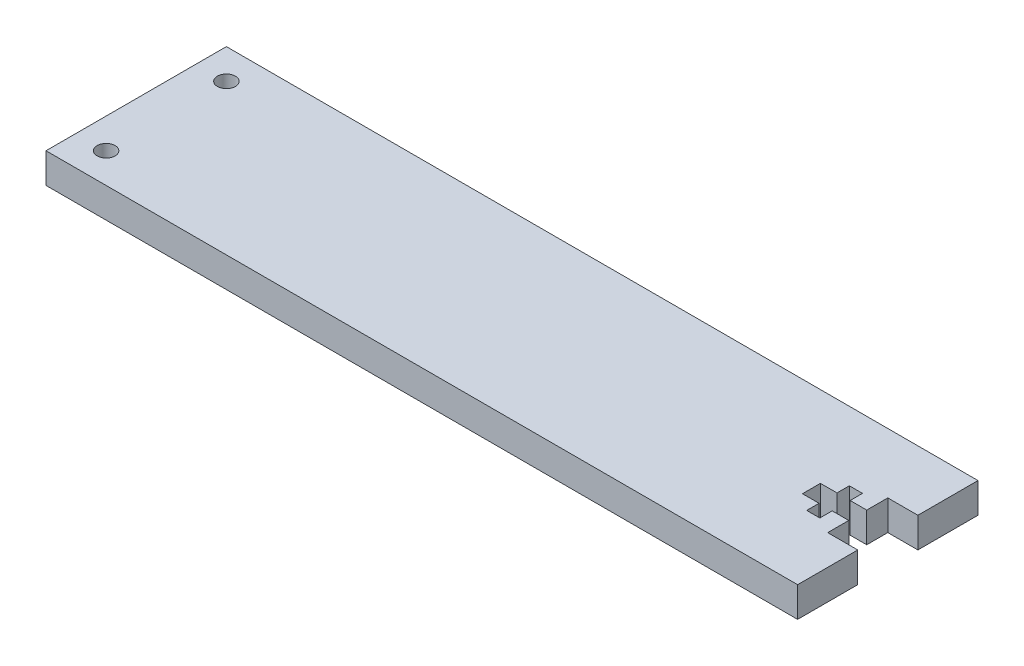
SolidWorks part; units mm, degrees
material "Beech"
ref_plane "Front Plane" through (0, 0, 0) normal (0, 0, 1) x (1, 0, 0)
ref_plane "Top Plane" through (0, 0, 0) normal (0, 1, 0) x (1, 0, 0)
ref_plane "Right Plane" through (0, 0, 0) normal (1, 0, 0) x (0, 0, -1)
sketch "Sketch1" plane through (0, 0, 0) normal (0, 1, 0) x (1, 0, 0)
  line L1 (-79.375, -19.05) -> (79.375, -19.05)
  line L2 (-79.375, -19.05) -> (-79.375, 19.05)
  line L3 (-79.375, 19.05) -> (79.375, 19.05)
  line L4 (79.375, -19.05) -> (79.375, 19.05)
  line L5 (-79.375, -19.05) -> (79.375, 19.05) construction
  line L6 (-79.375, 19.05) -> (79.375, -19.05) construction
  point P0 (0, 0)
  dimension "D1" = 158.75
  dimension "D2" = 38.1
extrude "Boss-Extrude1" add sketch "Sketch1" along normal mid plane 6.35
sketch "Sketch2" plane through (0, 3.175, 0) normal (0, 1, 0) x (1, 0, 0)
  line L0 (79.375, -6.35) -> (79.375, 6.35)
  line L1 (79.375, -6.35) -> (73.025, -6.35)
  line L2 (73.025, -6.35) -> (73.025, -1.8986)
  line L3 (79.375, 6.35) -> (73.025, 6.35)
  line L4 (73.025, 1.8987) -> (73.025, 6.35)
  line L5 (73.025, 1.8987) -> (69.5246, 1.8986)
  line L6 (63.246, 1.8986) -> (63.246, -1.8986)
  line L7 (73.025, -1.8986) -> (69.5246, -1.8986)
  line L8 (69.5246, -1.8986) -> (69.5246, -4.5045)
  line L9 (69.5246, -4.5045) -> (66.7464, -4.5045)
  line L10 (66.7464, -4.5045) -> (66.7464, -1.8986)
  line L11 (66.7464, -1.8986) -> (63.246, -1.8986)
  line L12 (69.5246, 1.8986) -> (69.5246, 4.5045)
  line L13 (69.5246, 4.5045) -> (66.7464, 4.5045)
  line L14 (66.7464, 4.5045) -> (66.7464, 1.8986)
  line L15 (66.7464, 1.8986) -> (63.246, 1.8986)
  line L16 (79.375, -19.05) -> (79.375, 19.05) construction
  line L17 (-79.375, 0) -> (79.375, 0) construction
  line L18 (-79.375, 19.05) -> (-79.375, -19.05) construction
  line L19 (63.246, 0) -> (79.375, 0) construction
  dimension "D1" = 6.35
  dimension "D2" = 9.779
  dimension "D3" = 3.7973
  dimension "D4" = 2.7783
  dimension "D5" = 12.7
  dimension "D6" = 4.5045
extrude "Cut-Extrude1" cut sketch "Sketch2" against normal up to next
hole_wizard "#6 Clearance Hole1" positions "Sketch4" profile "Sketch3" hole size "#6" standard "ANSI Inch" end condition up to next
sketch "Sketch4" plane through (0, 3.175, 0) normal (0, 1, 0) x (1, 0, 0)
  line L0 (0, 19.05) -> (0, -19.05) construction
  line L1 (79.375, 19.05) -> (-79.375, 19.05) construction
  line L2 (-79.375, -19.05) -> (79.375, -19.05) construction
  line L4 (-79.375, 19.05) -> (-79.375, -19.05) construction
  line L5 (-79.375, 0) -> (41.275, 0) construction
  point P0 (-73.025, -12.7)
  dimension "D1" = 25.4
  dimension "D2" = 6.35
sketch "Sketch3" plane through (-73.025, 3.175, 12.7) normal (1, 0, 0) x (0, 0, 1)
  line L0 (0, 0) -> (0, 6.35)
  line L1 (0, 6.35) -> (1.8986, 6.35)
  line L2 (1.8986, 6.35) -> (1.8986, 0)
  line L5 (1.8986, 0) -> (0, 0)
  line L11 (0, -6.35) -> (0, 107.95) construction
  dimension "Thru Hole Dia." = 3.7973
  dimension "Thru Hole Depth" = 6.35
mirror "Mirror1" about plane through (0, 0, 0) normal (0, 0, 1) of "#6 Clearance Hole1"
